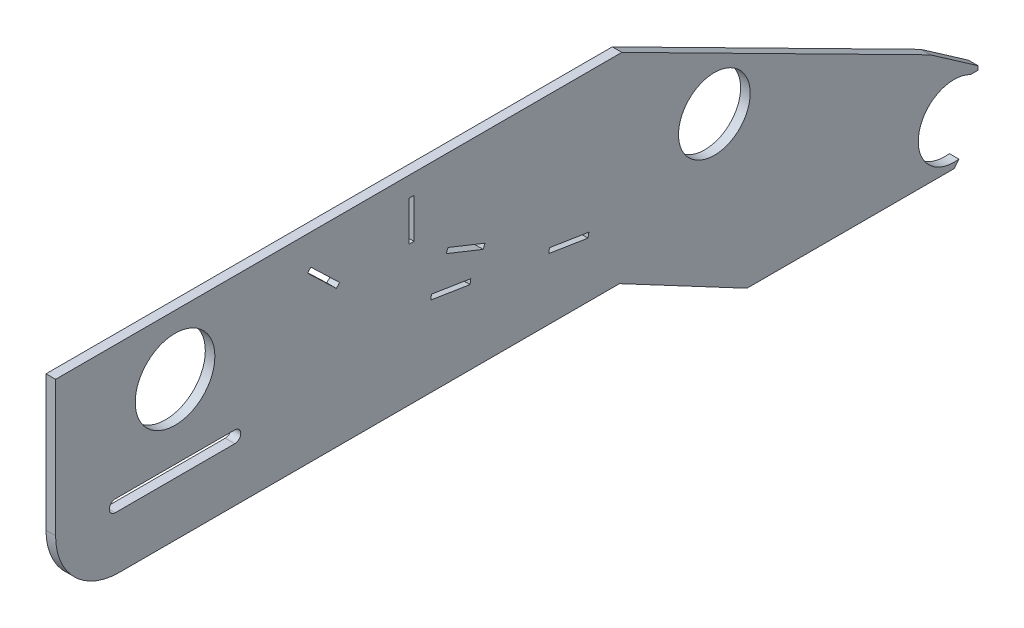
SolidWorks part; units mm, degrees
material "Q355"
ref_plane "前视基准面" through (0, 0, 0) normal (0, 0, 1) x (1, 0, 0)
ref_plane "上视基准面" through (0, 0, 0) normal (0, 1, 0) x (1, 0, 0)
ref_plane "右视基准面" through (0, 0, 0) normal (1, 0, 0) x (0, 0, -1)
sketch "草图1" plane through (0, 0, 0) normal (1, 0, 0) x (0, 0, -1)
  line L0 (-150, 75) -> (560.8807, 75)
  line L1 (560.8807, 75) -> (948, -121.2111)
  line L2 (-150, 75) -> (-150, -175)
  line L3 (-150, -175) -> (558, -175)
  line L4 (558, -175) -> (718, -260)
  line L5 (718, -260) -> (978, -260)
  line L6 (948, -121.2111) -> (1008, -163)
  line L7 (978, -260) -> (984, -252.5982)
  line L9 (998.6155, -168) -> (1008, -168)
  line L10 (1008, -168) -> (1008, -163)
  circle A0 centre (0, 0) radius 50
  circle A1 centre (677, -50) radius 45
  arc A2 (998.6155, -168) -> (984, -252.5982) centre (978, -208) ccw
  dimension "D3" = 100
  dimension "D4" = 90
  dimension "D5" = 301
  dimension "D7" = 90
  dimension "D21" = 978
  dimension "D18" = 30
  dimension "D12" = 160
  dimension "D2" = 50
  dimension "D6" = 158
  dimension "D8" = 75
  dimension "D9" = 150
  dimension "D10" = 250
  dimension "D11" = 335
  dimension "D13" = 260
  dimension "D14" = 6
  dimension "D15" = 710.8807
  dimension "D16" = 196.2111
  dimension "D17" = 60
  dimension "D19" = 40
  dimension "D20" = 5
extrude "凸台-拉伸1" add sketch "草图1" along normal blind 12
fillet "圆角1" radius 80 1 edges at (6, -175, 150)
sketch "草图3" plane through (12, 0, 0) normal (1, 0, 0) x (0, 0, -1)
  line L0 (-75, -100) -> (75, -100) construction
  line L1 (-75, -92.5) -> (75, -92.5)
  line L2 (-75, -107.5) -> (75, -107.5)
  line L3 (-150, 75) -> (-150, -95) construction
  line L4 (560.8807, 75) -> (-150, 75) construction
  arc A0 (-75, -92.5) -> (-75, -107.5) centre (-75, -100) ccw
  arc A1 (75, -107.5) -> (75, -92.5) centre (75, -100) ccw
  point P2 (0, -100)
  dimension "D3" = 7.5
  dimension "D1" = 75
  dimension "D2" = 175
  dimension "D4" = 150
extrude "切除-拉伸1" cut sketch "草图3" against normal blind 12
sketch "草图4" plane through (12, 0, 0) normal (1, 0, 0) x (0, 0, -1)
  line L0 (170.5107, 36.6271) -> (206.58, 2.0005)
  line L1 (170.5107, 36.6271) -> (166.3555, 32.2987)
  line L2 (206.58, 2.0005) -> (202.4249, -2.3279)
  line L3 (166.3555, 32.2987) -> (202.4249, -2.3279)
  line L4 (294, 50) -> (294, 0)
  line L5 (294, 50) -> (300, 50)
  line L6 (294, 0) -> (300, 0)
  line L7 (300, 50) -> (300, 0)
  line L12 (340.4238, -33.5695) -> (386.8477, -52.1391)
  line L13 (340.4238, -33.5695) -> (342.6522, -27.9987)
  line L14 (386.8477, -52.1391) -> (389.076, -46.5682)
  line L15 (342.6522, -27.9987) -> (389.076, -46.5682)
  line L16 (470.0601, -91.9362) -> (519.4397, -99.7884)
  line L17 (470.0601, -91.9362) -> (469.1178, -97.8618)
  line L18 (519.4397, -99.7884) -> (518.4974, -105.7139)
  line L19 (469.1178, -97.8618) -> (518.4974, -105.7139)
  line L22 (321.9213, -68.3797) -> (371.3009, -76.2319)
  line L23 (321.9213, -68.3797) -> (320.9791, -74.3053)
  line L24 (371.3009, -76.2319) -> (370.3587, -82.1574)
  line L25 (320.9791, -74.3053) -> (370.3587, -82.1574)
  circle A1 centre (0, 0) radius 50 construction
  dimension "D3" = 300
  dimension "D6" = 6
  dimension "D7" = 50
  dimension "D10" = 100
extrude "切除-拉伸2" cut sketch "草图4" against normal blind 12
